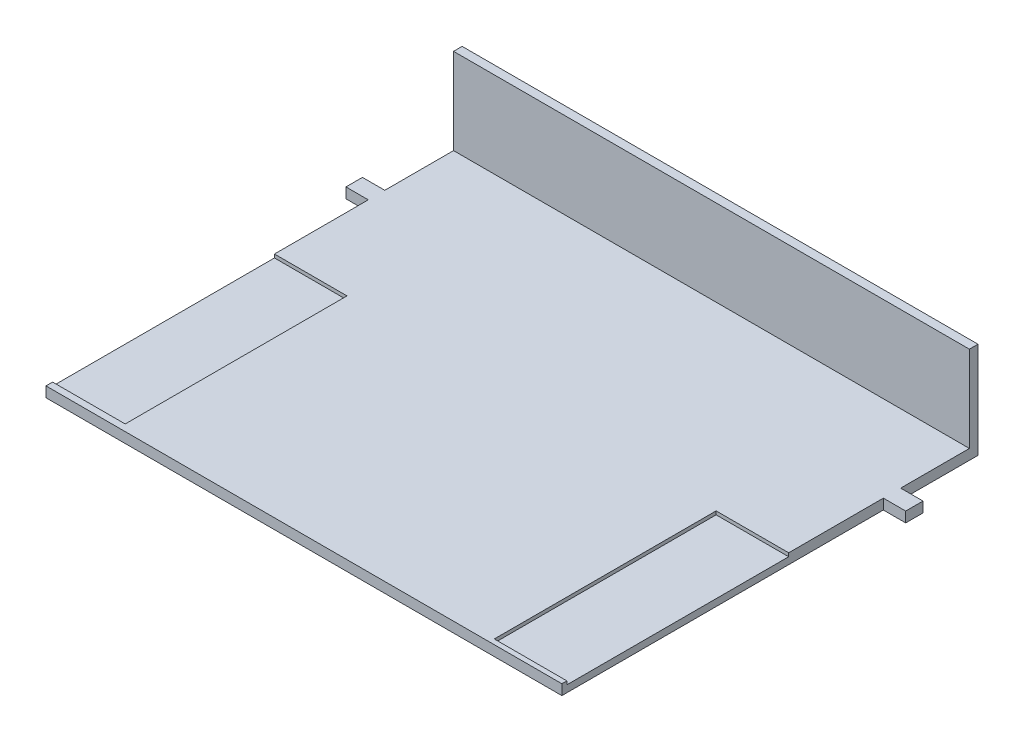
SolidWorks part; units mm, degrees
ref_plane "Front Plane" through (0, 0, 0) normal (0, 0, 1) x (1, 0, 0)
ref_plane "Top Plane" through (0, 0, 0) normal (0, 1, 0) x (1, 0, 0)
ref_plane "Right Plane" through (0, 0, 0) normal (1, 0, 0) x (0, 0, -1)
sketch "Sketch1" plane through (0, 0, 0) normal (0, 0, 1) x (1, 0, 0)
  line L1 (0, 0) -> (150, 0)
  line L2 (0, 0) -> (0, 3)
  line L3 (0, 3) -> (150, 3)
  line L4 (150, 0) -> (150, 3)
  dimension "D1" = 3
  dimension "D2" = 150
extrude "Boss-Extrude1" add sketch "Sketch1" along normal blind 121 contours L2 L1 L4 L3
ref_plane "Plane1" through (150, 3, 121) normal (0, 0, -1) x (-1, 0, 0)
sketch "Sketch3" plane through (0, 3, 0) normal (0, 1, 0) x (1, 0, 0)
  line L0 (0, -119.0747) -> (21.1, -119.0747)
  line L1 (0, -121) -> (0, 0) construction
  line L2 (21.1, -119.0747) -> (21.1, -54.5747)
  line L3 (21.1, -54.5747) -> (0, -54.5747)
  line L4 (0, -54.5747) -> (0, -119.0747)
extrude "Cut-Extrude1" cut sketch "Sketch3" against normal blind 1 contours L4 L0 L2 L3
sketch "Sketch4" plane through (0, 3, 0) normal (0, 1, 0) x (1, 0, 0)
  line L0 (128.9, -55.0483) -> (150, -55.0483)
  line L1 (150, -121) -> (150, 0) construction
  line L2 (150, -119.5483) -> (128.9, -119.5483)
  line L3 (150, -119.5483) -> (150, -55.0483)
  line L4 (128.9, -119.5483) -> (128.9, -55.0483)
extrude "Cut-Extrude2" cut sketch "Sketch4" against normal blind 1
ref_plane "Plane2" through (150, 3, 0) normal (0, 0, -1) x (-1, 0, 0)
sketch "Sketch6" plane through (0, 0, 0) normal (0, 1, 0) x (1, 0, 0)
  line L0 (0, -22.4873) -> (-6.5, -22.4873)
  line L1 (0, -54.5747) -> (0, 0) construction
  line L2 (-6.5, -22.4873) -> (-6.5, -27.2873)
  line L3 (-6.5, -27.2873) -> (0, -27.2873)
  line L4 (0, -27.2873) -> (0, -22.4873)
  line L5 (150, -22.4873) -> (156.5, -22.4873)
  line L6 (150, -121) -> (150, 0) construction
  line L7 (156.5, -22.4873) -> (156.5, -27.2873)
  line L8 (156.5, -27.2873) -> (150, -27.2873)
  line L9 (150, -27.2873) -> (150, -22.4873)
extrude "Boss-Extrude5" add sketch "Sketch6" along normal blind 3 contours L4 L0 L2 L3
sketch "Sketch9" plane through (0, 3, 0) normal (0, 1, 0) x (1, 0, 0)
  line L1 (150, -55.0483) -> (150, 0) construction
  line L2 (150, -22.4873) -> (150, -27.5241)
  line L3 (150, -27.5241) -> (156.5, -27.5241)
  line L4 (156.5, -27.5241) -> (156.5, -22.4873)
  line L5 (156.5, -22.4873) -> (150, -22.4873)
extrude "Boss-Extrude7" add sketch "Sketch9" against normal blind 3
sketch "Sketch10" plane through (0, 0, 0) normal (0, 0, -1) x (-1, 0, 0)
  line L0 (-150, 3) -> (-150, 28)
  line L1 (-150, 28) -> (0, 28)
  line L2 (0, 28) -> (0, 3)
  line L3 (-150, 3) -> (0, 3)
extrude "Boss-Extrude8" add sketch "Sketch10" against normal blind 2.5
sketch "Sketch12" plane through (0, 3, 0) normal (0, 1, 0) x (1, 0, 0)
  circle A0 centre (126.827, -57.5427) radius 1.5
  circle A1 centre (126.827, -82.3903) radius 1.5
  circle A2 centre (126.827, -105.463) radius 1.5
  circle A3 centre (22.8222, -57.5427) radius 1.5
  circle A4 centre (22.8222, -82.3903) radius 1.5
  circle A5 centre (22.8222, -105.463) radius 1.5
  circle A7 centre (71.0208, -116.9209) radius 3
  circle A8 centre (31.294, -97.8274) radius 3
  circle A9 centre (31.294, -73.0679) radius 3
  circle A10 centre (120.5816, -73.0679) radius 3
  circle A11 centre (120.5816, -97.8274) radius 3
  point P22 (0, 0)
